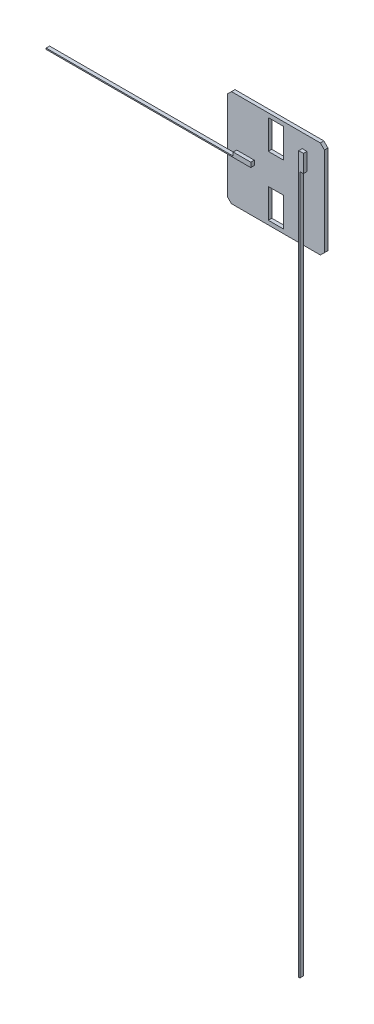
SolidWorks part; units mm, degrees
ref_plane "Front Plane" through (0, 0, 0) normal (0, 0, 1) x (1, 0, 0)
ref_plane "Top Plane" through (0, 0, 0) normal (0, 1, 0) x (1, 0, 0)
ref_plane "Right Plane" through (0, 0, 0) normal (1, 0, 0) x (0, 0, -1)
sketch "Sketch1" plane through (0, 0, 0) normal (0, 0, 1) x (1, 0, 0)
  line L1 (41.5, -41.5) -> (-41.5, -41.5)
  line L2 (41.5, -41.5) -> (41.5, 41.5)
  line L3 (41.5, 41.5) -> (-41.5, 41.5)
  line L4 (-41.5, -41.5) -> (-41.5, 41.5)
  line L5 (41.5, -41.5) -> (-41.5, 41.5) construction
  line L6 (41.5, 41.5) -> (-41.5, -41.5) construction
  point P0 (0, 0)
  dimension "D1" = 83
  dimension "D2" = 83
extrude "Boss-Extrude1" add sketch "Sketch1" along normal blind 3
sketch "Sketch2" plane through (0, 0, 3) normal (0, 0, 1) x (1, 0, 0)
  line L1 (-6.5, 38) -> (6.5, 38)
  line L2 (-6.5, 38) -> (-6.5, 13)
  line L3 (-6.5, 13) -> (6.5, 13)
  line L4 (6.5, 38) -> (6.5, 13)
  line L6 (0, 0) -> (65.5983, 0) construction
  line L7 (6.5, -38) -> (6.5, -13)
  line L8 (-6.5, -13) -> (6.5, -13)
  line L9 (-6.5, -38) -> (-6.5, -13)
  line L10 (-6.5, -38) -> (6.5, -38)
  line L11 (0, 0) -> (0, 70.3331) construction
  dimension "D1" = 13
  dimension "D2" = 6.5
  dimension "D3" = 13
  dimension "D4" = 25
extrude "Cut-Extrude1" cut sketch "Sketch2" against normal blind 3
chamfer "Chamfer1" distance 3.5 angle 45 4 edges at (-41.5, -41.5, 1.5) (41.5, -41.5, 1.5) (41.5, 41.5, 1.5) (-41.5, 41.5, 1.5)
sketch "Sketch3" plane through (0, 0, 3) normal (0, 0, 1) x (1, 0, 0)
  line L0 (41.5, -38) -> (41.5, 38) construction
  line L1 (-33.5, 0.5) -> (-18.5, 0.5)
  line L2 (-33.5, 0.5) -> (-33.5, -2.5)
  line L3 (-33.5, -2.5) -> (-18.5, -2.5)
  line L4 (-18.5, 0.5) -> (-18.5, -2.5)
  line L5 (38, 41.5) -> (-38, 41.5) construction
  line L6 (-41.5, 38) -> (-41.5, -38) construction
  line L7 (23.5, 29.5) -> (26.5, 29.5)
  line L8 (23.5, 29.5) -> (23.5, 14.5)
  line L9 (23.5, 14.5) -> (26.5, 14.5)
  line L10 (26.5, 29.5) -> (26.5, 14.5)
  dimension "D1" = 15
  dimension "D2" = 3
  dimension "D3" = 60
  dimension "D4" = 41
  dimension "D5" = 3
  dimension "D6" = 15
  dimension "D7" = 12
  dimension "D8" = 65
extrude "Boss-Extrude2" add sketch "Sketch3" along normal blind 3
sketch "Sketch4" plane through (23.5, 0, 0) normal (-1, 0, 0) x (0, 0, 1)
  line L1 (6, -582.5) -> (3, -582.5)
  line L2 (6, -582.5) -> (6, 29.5)
  line L3 (6, 29.5) -> (3, 29.5)
  line L4 (3, -582.5) -> (3, 29.5)
  line L5 (6, 29.5) -> (3, 29.5) construction
  line L6 (3, 29.5) -> (3, 14.5) construction
  dimension "D1" = 3
  dimension "D2" = 612
extrude "Boss-Extrude3" add sketch "Sketch4" along normal blind 1
sketch "Sketch5" plane through (0, -2.5, 0) normal (0, -1, 0) x (1, 0, 0)
  line L1 (-193.5, 3) -> (-18.5, 3)
  line L2 (-193.5, 3) -> (-193.5, 6)
  line L3 (-193.5, 6) -> (-18.5, 6)
  line L4 (-18.5, 3) -> (-18.5, 6)
  line L5 (-18.5, 6) -> (-18.5, 3) construction
  dimension "D1" = 3
  dimension "D2" = 175
extrude "Boss-Extrude4" add sketch "Sketch5" along normal blind 1
